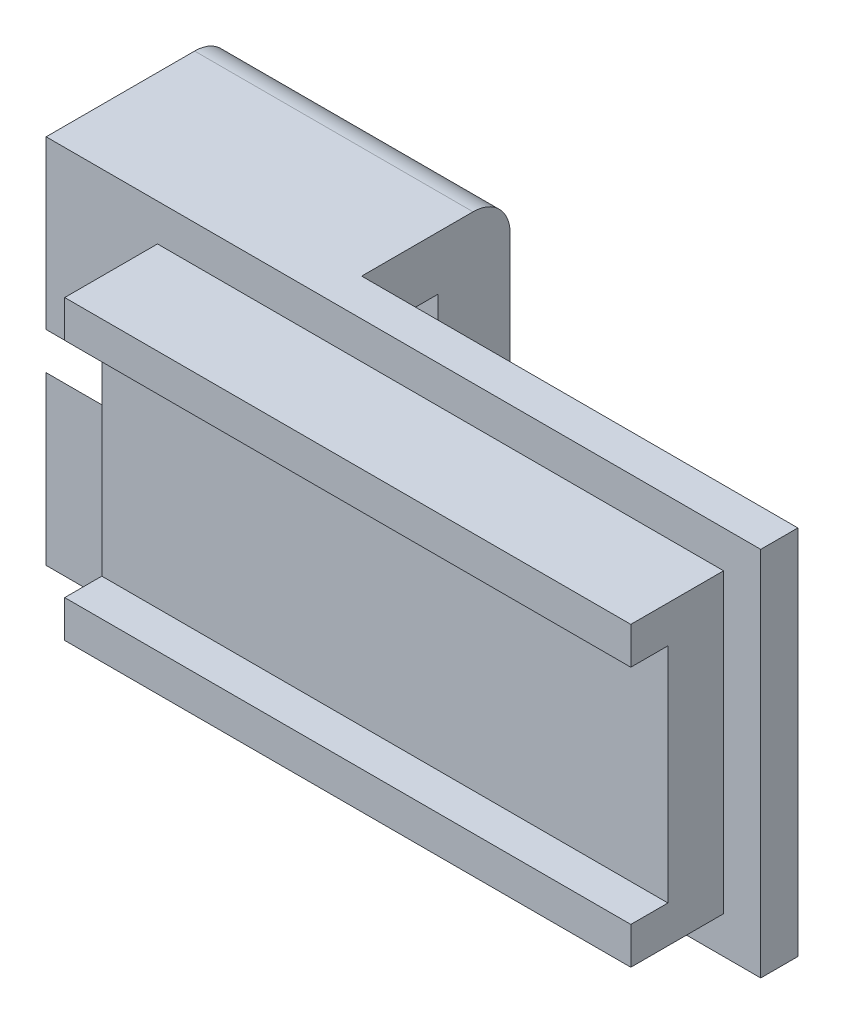
SolidWorks part; units mm, degrees
ref_plane "Front Plane" through (0, 0, 0) normal (1, 0, 0) x (0, 1, 0)
ref_plane "Top Plane" through (0, 0, 0) normal (0, 0, 1) x (0, 1, 0)
ref_plane "Right Plane" through (0, 0, 0) normal (0, 1, 0) x (-1, 0, 0)
sketch "Sketch1" plane through (0, 0, 0) normal (1, 0, 0) x (0, 1, 0)
  line L1 (-10, 5) -> (10, 5)
  line L2 (-10, 5) -> (-10, -5)
  line L3 (-10, -5) -> (10, -5)
  line L4 (10, 5) -> (10, -5)
  line L5 (-10, 5) -> (10, -5) construction
  line L6 (-10, -5) -> (10, 5) construction
  point P0 (0, 0)
  dimension "D1" = 10
  dimension "D2" = 20
extrude "Boss-Extrude1" add sketch "Sketch1" along normal blind 38.5
sketch "Sketch5" plane through (0, 0, 0) normal (0, 0, 1) x (0, 1, 0)
  line L1 (-8, -6) -> (8, -6)
  line L2 (-8, -6) -> (-8, -36.5)
  line L3 (-8, -36.5) -> (8, -36.5)
  line L4 (8, -6) -> (8, -36.5)
  line L5 (-10, -38.5) -> (-10, 0) construction
  line L6 (10, -38.5) -> (10, 0) construction
  line L7 (10, -38.5) -> (-10, -38.5) construction
  line L8 (10, 0) -> (-10, 0) construction
  dimension "D1" = 2
  dimension "D2" = 2
  dimension "D3" = 2
  dimension "D4" = 6
extrude "Boss-Extrude2" add sketch "Sketch5" along normal blind 8
sketch "Sketch2" plane through (0, 0, 0) normal (1, 0, 0) x (0, 1, 0)
  circle A0 centre (0, 0) radius 5.1
  dimension "D1" = 10.2
extrude "Cut-Extrude3" cut sketch "Sketch2" along normal blind 10
fillet "Fillet1" radius 2 2 edges at (19.25, -10, -5) (19.25, 10, -5)
sketch "Sketch6" plane through (0, 0, -5) normal (0, 0, -1) x (1, 0, 0)
  line L0 (0, 10) -> (38.5, 10) construction
  line L1 (15, 10) -> (38.5, 10)
  line L2 (15, 10) -> (15, -10)
  line L3 (15, -10) -> (38.5, -10)
  line L4 (38.5, 10) -> (38.5, -10)
  line L5 (10, 5.1) -> (10, -5.1) construction
  dimension "D1" = 5
extrude "Cut-Extrude4" cut sketch "Sketch6" against normal blind 8
sketch "Sketch7" plane through (15, 0, 0) normal (1, 0, 0) x (0, 1, 0)
  line L0 (0, 0) -> (6, 0) construction
  line L1 (0, -7.15) -> (0, 7.15) construction
  line L2 (4.9, 1.1) -> (7.1, 1.1)
  line L3 (4.9, 1.1) -> (4.9, -1.1)
  line L4 (4.9, -1.1) -> (7.1, -1.1)
  line L5 (7.1, 1.1) -> (7.1, -1.1)
  line L6 (4.9, 1.1) -> (7.1, -1.1) construction
  line L7 (4.9, -1.1) -> (7.1, 1.1) construction
  line L8 (-4.9, -1.1) -> (-7.1, -1.1)
  line L9 (-7.1, 1.1) -> (-7.1, -1.1)
  line L10 (-4.9, 1.1) -> (-7.1, 1.1)
  line L11 (-4.9, 1.1) -> (-4.9, -1.1)
  dimension "D1" = 6
  dimension "D2" = 2.2
  dimension "D3" = 2.2
extrude "Cut-Extrude5" cut sketch "Sketch7" against normal blind 3
sketch "Sketch8" plane through (0, 0, 8) normal (0, 0, 1) x (1, 0, 0)
  line L0 (36.5, -8) -> (36.5, 8) construction
  line L1 (6, 8) -> (36.5, 8)
  line L2 (6, 8) -> (6, 6)
  line L3 (6, 6) -> (36.5, 6)
  line L4 (36.5, 8) -> (36.5, 6)
  line L6 (6, -8) -> (36.5, -8)
  line L7 (6, -8) -> (6, -6)
  line L8 (6, -6) -> (36.5, -6)
  line L9 (36.5, -8) -> (36.5, -6)
  dimension "D1" = 2
  dimension "D2" = 2
extrude "Boss-Extrude3" add sketch "Sketch8" along normal blind 2 contours L7 L6 L9 L8 | L2 L1 L4 L3
